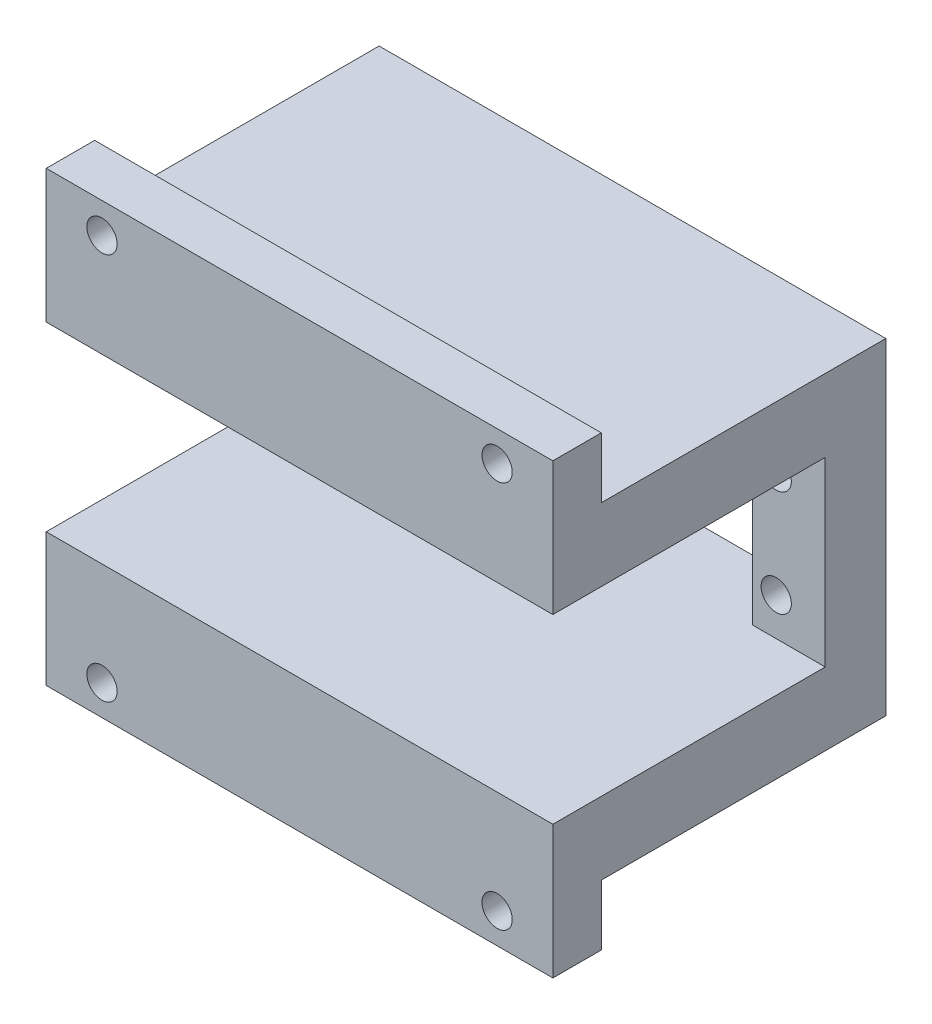
SolidWorks part; units mm, degrees
ref_plane "Alzado" through (0, 0, 0) normal (0, 0, 1) x (1, 0, 0)
ref_plane "Planta" through (0, 0, 0) normal (0, 1, 0) x (1, 0, 0)
ref_plane "Vista lateral" through (0, 0, 0) normal (1, 0, 0) x (0, 0, -1)
sketch "Croquis1" plane through (0, 0, 0) normal (0, 0, 1) x (1, 0, 0)
  line L0 (-33.0811, 4.5228) -> (-33.0811, -3.7634)
  line L1 (38.6189, 38.2366) -> (-21.0811, 38.2366)
  line L2 (-21.0811, 38.2366) -> (-21.0811, 26.7366)
  line L3 (-21.0811, 8.2366) -> (15.8485, 8.2366)
  line L4 (-8.3179, 23.2366) -> (8.5, 23.2366) construction
  line L5 (-8.3179, 23.2366) -> (-21.0811, 23.2366) construction
  line L6 (-24.6811, 19.7366) -> (-21.0811, 19.7366)
  line L7 (-24.6811, 26.7366) -> (-21.0811, 26.7366)
  line L8 (-33.0811, -3.7634) -> (50.6189, -3.7634)
  line L9 (-33.0811, 7.2653) -> (-33.0811, 50.2366)
  line L10 (-33.0811, 50.2366) -> (50.6189, 50.2366)
  line L11 (-21.0811, 19.7366) -> (-21.0811, 8.2366)
  line L12 (50.6189, -3.7634) -> (50.6189, 4.5228)
  line L16 (8.5, 23.2366) -> (39.3302, 23.2366) construction
  line L18 (-33.0811, 7.2653) -> (-33.0811, 4.5228)
  line L21 (38.6189, 8.2366) -> (38.6189, 38.2366)
  line L22 (50.6189, 4.5228) -> (50.6189, 50.2366)
  line L23 (-21.0811, 19.7366) -> (-21.0811, 26.7366) construction
  line L27 (8.7689, 38.2366) -> (8.7689, 8.2366) construction
  line L29 (15.8485, 8.2366) -> (38.6189, 8.2366)
  circle A0 centre (-24.9811, 14.4866) radius 2.5
  circle A1 centre (-24.9811, 31.9866) radius 2.5
  circle A5 centre (42.5189, 31.9866) radius 2.5
  circle A6 centre (42.5189, 14.4866) radius 2.5
  arc A8 (-24.6811, 26.7366) -> (-24.6811, 19.7366) centre (-24.7797, 23.2366) ccw
  point P7 (38.6189, 23.2366)
  point P16 (-28.2811, 23.2366)
  point P29 (8.7689, 23.2366)
  point P30 (0, 0.0228)
  point P33 (0.091, 23.2366)
  point P51 (8.7689, 38.2366)
  dimension "D4" = 12
  dimension "D3" = 7
  dimension "D6" = 12
  dimension "D5" = 17.5
  dimension "D11" = 7.2
  dimension "D7" = 59.7
  dimension "D8" = 67.5
  dimension "D1" = 30
  dimension "D2" = 12
  dimension "D10" = 12
extrude "Saliente-Extruir1" add sketch "Croquis1" along normal blind 10
sketch "Croquis2" plane through (0, 0, 10) normal (0, 0, 1) x (1, 0, 0)
  line L0 (-33.0811, -3.7634) -> (50.6189, -3.7634) construction
  line L1 (-33.0811, 8.2366) -> (50.6189, 8.2366)
  line L2 (-33.0811, 8.2366) -> (-33.0811, -3.7634)
  line L3 (-33.0811, -3.7634) -> (50.6189, -3.7634)
  line L4 (50.6189, 8.2366) -> (50.6189, -3.7634)
  line L5 (38.6189, 23.2366) -> (-22.4716, 23.2366) construction
  line L6 (38.6189, 8.2366) -> (38.6189, 38.2366) construction
  line L7 (50.6189, 38.2366) -> (50.6189, 50.2366)
  line L8 (-33.0811, 50.2366) -> (50.6189, 50.2366)
  line L9 (-33.0811, 38.2366) -> (-33.0811, 50.2366)
  line L10 (-33.0811, 38.2366) -> (50.6189, 38.2366)
  line L11 (50.6189, -3.7634) -> (50.6189, 50.2366) construction
  line L12 (-33.0811, 50.2366) -> (-33.0811, -3.7634) construction
extrude "Saliente-Extruir2" add sketch "Croquis2" along normal blind 45
sketch "Croquis3" plane through (0, -3.7634, 0) normal (0, -1, 0) x (1, 0, 0)
  line L0 (50.6189, 55) -> (50.6189, 0) construction
  line L1 (-33.0811, 55) -> (50.6189, 55)
  line L2 (-33.0811, 55) -> (-33.0811, 47)
  line L3 (-33.0811, 47) -> (50.6189, 47)
  line L4 (50.6189, 55) -> (50.6189, 47)
  dimension "D1" = 8
extrude "Saliente-Extruir3" add sketch "Croquis3" along normal blind 10
sketch "Croquis4" plane through (0, 0, 47) normal (0, 0, -1) x (-1, 0, 0)
  line L0 (-8.7689, -13.7634) -> (-8.7689, -3.7634) construction
  line L1 (33.0811, -13.7634) -> (-50.6189, -13.7634) construction
  line L2 (33.0811, -3.7634) -> (-50.6189, -3.7634) construction
  line L3 (-8.7689, -8.7634) -> (-61.6022, -8.7634) construction
  circle A0 centre (-41.4101, -8.7634) radius 2.5
  circle A1 centre (23.8723, -8.7634) radius 2.5
  point P10 (0, 0)
  point P11 (-41.4101, -8.7634)
  dimension "D1" = 5
extrude "Cortar-Extruir1" cut sketch "Croquis4" against normal up to next
ref_plane "Plano1" through (0, 23.2366, 0) normal (0, 1, 0) x (1, 0, 0)
mirror "Simetría1" about plane through (0, 23.2366, 0) normal (0, 1, 0) of "Cortar-Extruir1", "Saliente-Extruir3"
